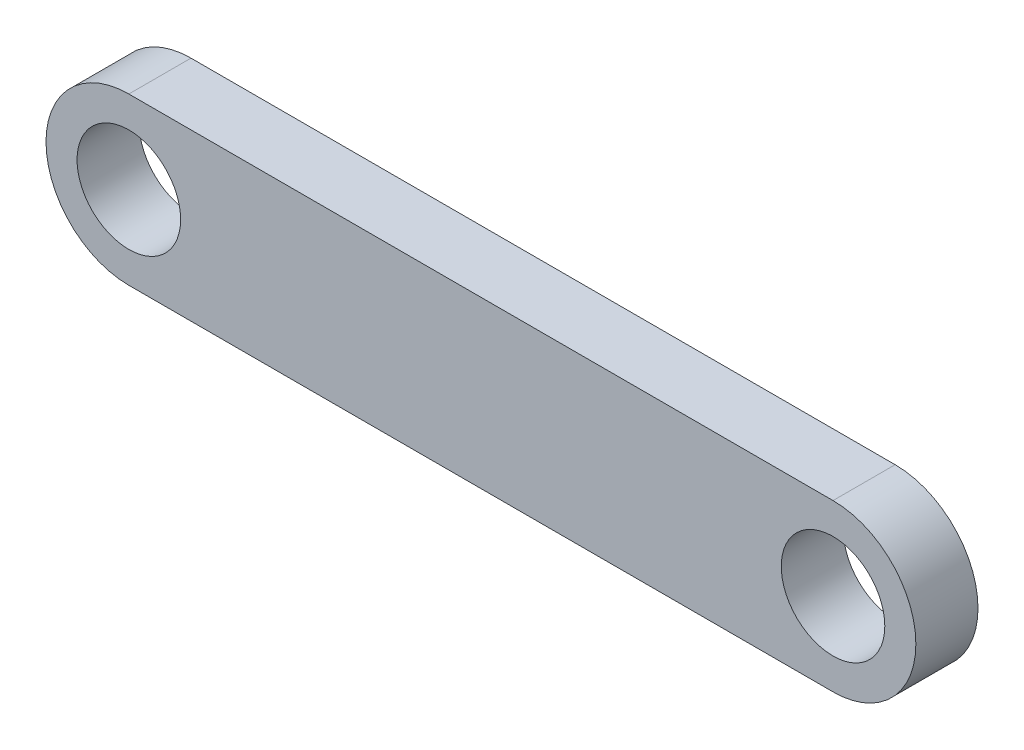
SolidWorks part; units mm, degrees
material "ABS"
ref_plane "Front Plane" through (0, 0, 0) normal (0, 0, 1) x (1, 0, 0)
ref_plane "Top Plane" through (0, 0, 0) normal (0, 1, 0) x (1, 0, 0)
ref_plane "Right Plane" through (0, 0, 0) normal (1, 0, 0) x (0, 0, -1)
sketch "Sketch1" plane through (0, 0, 0) normal (0, 0, 1) x (1, 0, 0)
  line L0 (0, 0) -> (-34, 0)
  dimension "D1" = 34
sketch "Sketch2" plane through (0, 0, 0) normal (0, 0, 1) x (1, 0, 0)
  line L0 (-34, 4) -> (0, 4)
  line L1 (-34, -4) -> (0, -4)
  circle A0 centre (-34, 0) radius 2.5
  circle A1 centre (0, 0) radius 2.5
  arc A2 (-34, 4) -> (-34, -4) centre (-34, 0) ccw
  arc A3 (0, -4) -> (0, 4) centre (0, 0) ccw
  dimension "D1" = 5
  dimension "D2" = 8
  dimension "D3" = 5
  dimension "D4" = 8
extrude "Boss-Extrude1" add sketch "Sketch2" along normal blind 3
